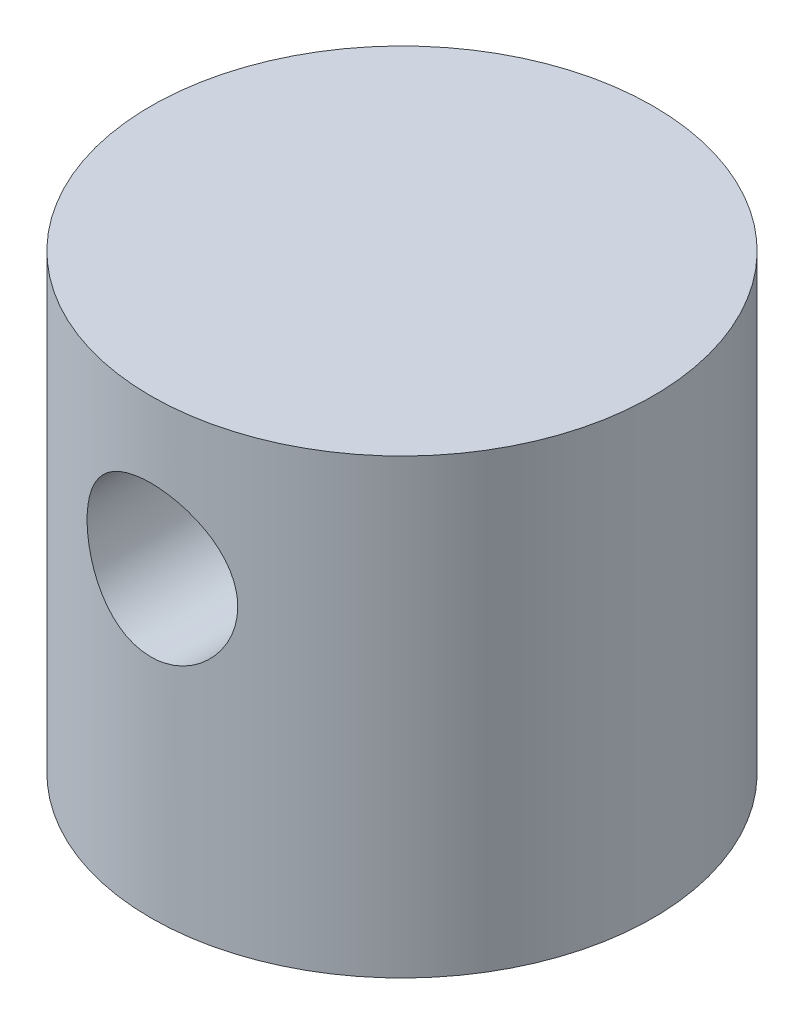
SolidWorks part; units mm, degrees
ref_plane "Front Plane" through (0, 0, 0) normal (0, 0, 1) x (1, 0, 0)
ref_plane "Top Plane" through (0, 0, 0) normal (0, 1, 0) x (1, 0, 0)
ref_plane "Right Plane" through (0, 0, 0) normal (1, 0, 0) x (0, 0, -1)
sketch "Sketch1" plane through (0, 0, 0) normal (0, 1, 0) x (1, 0, 0)
  circle A0 centre (0, 0) radius 12.7
  dimension "D1" = 25.4
extrude "Boss-Extrude1" add sketch "Sketch1" along normal blind 22.86
sketch "Sketch2" plane through (0, 0, 0) normal (0, 0, 1) x (1, 0, 0)
  line L0 (0, 22.86) -> (0, 15.24) construction
  line L1 (12.7, 22.86) -> (-12.7, 22.86) construction
  circle A0 centre (0, 15.24) radius 3.81
  dimension "D1" = 7.62
  dimension "D2" = 7.62
extrude "Cut-Extrude1" cut sketch "Sketch2" against normal through all both and the other way through all
